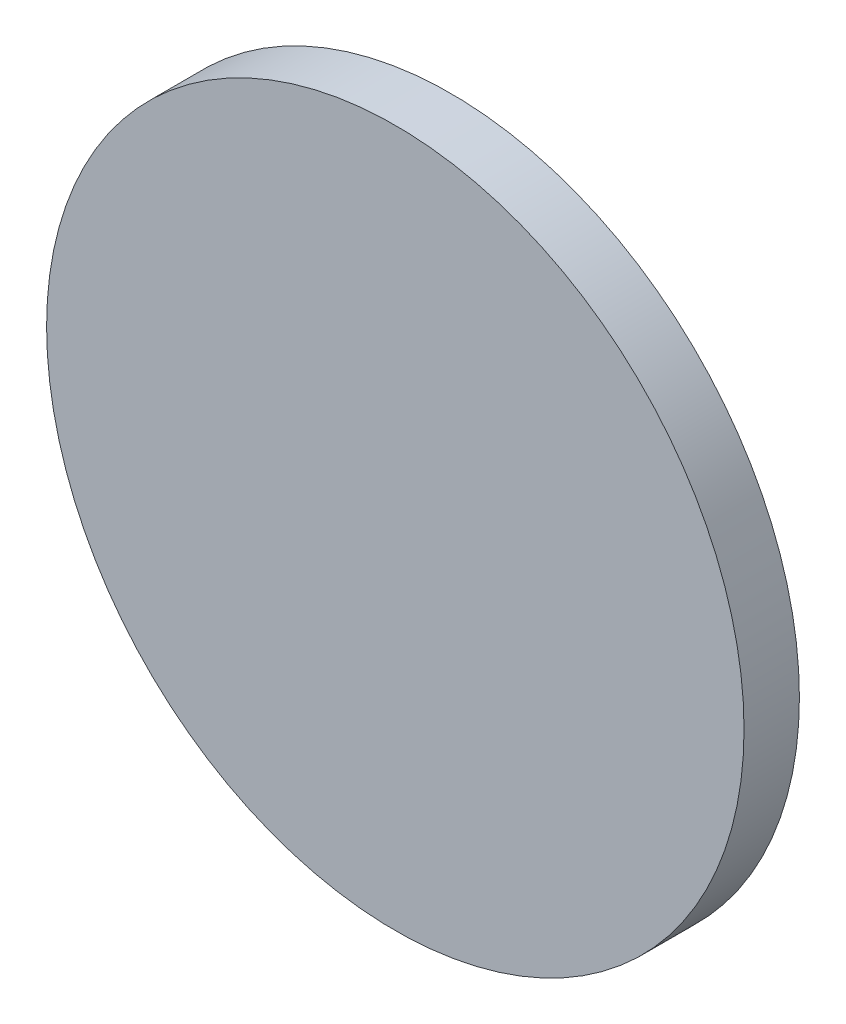
SolidWorks part; units mm, degrees
material "Acrylic (Medium-high impact)"
ref_plane "Front Plane" through (0, 0, 0) normal (0, 0, 1) x (1, 0, 0)
ref_plane "Top Plane" through (0, 0, 0) normal (0, 1, 0) x (1, 0, 0)
ref_plane "Right Plane" through (0, 0, 0) normal (1, 0, 0) x (0, 0, -1)
sketch "Sketch2" plane through (0, 0, 0) normal (0, 0, 1) x (1, 0, 0)
  circle A0 centre (0, 0) radius 20
  dimension "D1" = 40
extrude "Boss-Extrude1" add sketch "Sketch2" along normal blind 3.175
